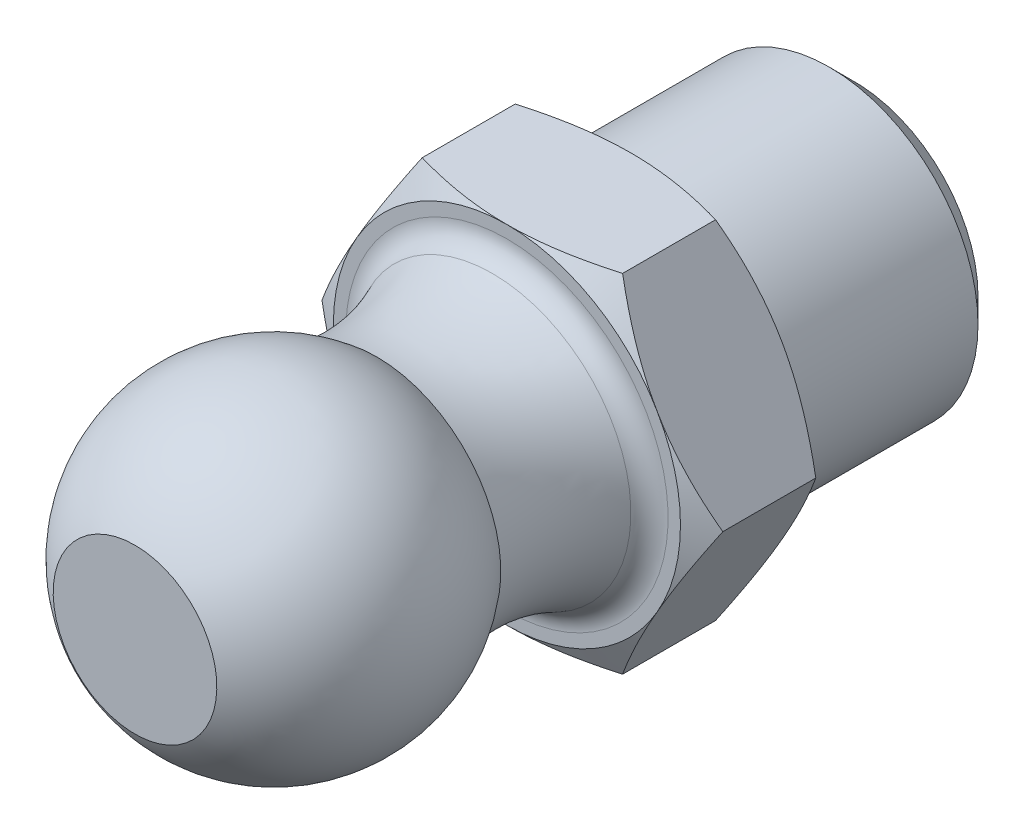
SolidWorks part; units mm, degrees
ref_plane "Přední rovina" through (0, 0, 0) normal (0, 0, 1) x (1, 0, 0)
ref_plane "Vrchní rovina" through (0, 0, 0) normal (0, 1, 0) x (1, 0, 0)
ref_plane "Pravá rovina" through (0, 0, 0) normal (1, 0, 0) x (0, 0, -1)
sketch "Skica1" plane through (0, 0, 0) normal (0, 0, 1) x (1, 0, 0)
  line L1 (4.0415, 0) -> (2.0207, 3.5)
  line L2 (2.0207, 3.5) -> (-2.0207, 3.5)
  line L3 (-2.0207, 3.5) -> (-4.0415, 0)
  line L4 (-4.0415, 0) -> (-2.0207, -3.5)
  line L5 (-2.0207, -3.5) -> (2.0207, -3.5)
  line L6 (2.0207, -3.5) -> (4.0415, 0)
  circle A0 centre (0, 0) radius 3.5 construction
  dimension "D1" = 7
extrude "Vysunout1" add sketch "Skica1" along normal mid plane 2.5
sketch "Skica2" plane through (0, 0, 0) normal (1, 0, 0) x (0, 0, -1)
  line L0 (-1.25, 0) -> (-2.3776, 0) construction
  line L1 (-1.25, 3.5) -> (-1.25, 5.1423)
  line L2 (-1.25, 5.1423) -> (-0.3018, 5.1423)
  line L3 (-0.3018, 5.1423) -> (-1.25, 3.5)
  dimension "D1" = 30
revolve "Odebrat otočením1" cut sketch "Skica2" angle 360 about L0
mirror "Zrcadlit1" about plane through (0, 0, 0) normal (0, 0, 1) of "Odebrat otočením1"
sketch "Skica3" plane through (0, 0, 0) normal (1, 0, 0) x (0, 0, -1)
  line L0 (-1.25, 0) -> (1.25, 0) construction
  line L1 (-1.25, 1.75) -> (-1.25, -1.75) construction
  line L2 (-1.25, 3.5) -> (-1.25, 1.75) construction
  line L3 (-1.25, 3.5) -> (-1.25, 1.75) construction
  line L4 (-8.75, 1.65) -> (-8.75, 0)
  line L5 (-8.75, 0) -> (-1.25, 0)
  line L6 (-1.25, 0) -> (-1.25, 3.25)
  line L7 (1.25, -1.75) -> (1.25, 1.75) construction
  arc A0 (-1.25, 3.25) -> (-1.5445, 2.7942) centre (-1.75, 3.25) cw
  arc A1 (-1.5445, 2.7942) -> (-3.8733, 2.5) centre (-3.1882, 6.4409) cw
  arc A2 (-3.8733, 2.5) -> (-8.75, 1.65) centre (-5.95, 0) ccw
  dimension "D2" = 6.5
  dimension "D4" = 4
  dimension "D7" = 0.5
  dimension "D1" = 5
  dimension "D3" = 2.8
  dimension "D5" = 6.5
  dimension "D6" = 7.5
revolve "Otočit kolem osy1" add sketch "Skica3" angle 360 about L0
sketch "Skica4" plane through (0, 0, -1.25) normal (0, 0, -1) x (-1, 0, 0)
  circle A0 centre (0, 0) radius 3
  dimension "D1" = 6
extrude "Vysunout2" add sketch "Skica4" along normal blind 4.5
cosmetic thread "Kosmetický závit1" parameters "D1"=2.9, "D2"=4.5
chamfer "Zkosit1" distance 0.5 angle 45 1 edges at (-3, 0, -5.75)
